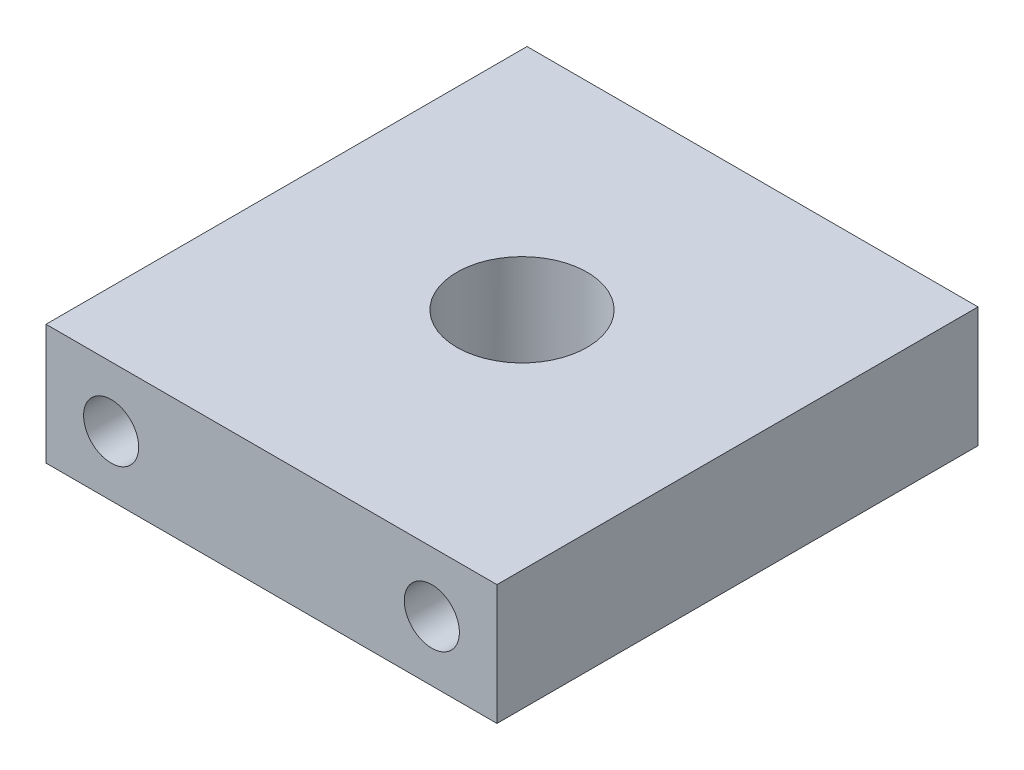
SolidWorks part; units mm, degrees
ref_plane "前视基准面" through (0, 0, 0) normal (0, 0, 1) x (1, 0, 0)
ref_plane "上视基准面" through (0, 0, 0) normal (0, 1, 0) x (1, 0, 0)
ref_plane "右视基准面" through (0, 0, 0) normal (1, 0, 0) x (0, 0, -1)
sketch "草图1" plane through (0, 0, 0) normal (0, 1, 0) x (1, 0, 0)
  line L1 (0, 0) -> (45, 0)
  line L2 (0, 0) -> (0, 48)
  line L3 (0, 48) -> (45, 48)
  line L4 (45, 0) -> (45, 48)
  dimension "D1" = 45
  dimension "D2" = 48
extrude "凸台-拉伸1" add sketch "草图1" along normal blind 12
sketch "草图2" plane through (0, 12, 0) normal (0, 1, 0) x (1, 0, 0)
  line L0 (22.5, 48) -> (22.5, 0) construction
  line L1 (45, 48) -> (0, 48) construction
  line L2 (0, 0) -> (45, 0) construction
  line L3 (0, 25) -> (45, 25) construction
  line L4 (0, 48) -> (0, 0) construction
  line L5 (45, 0) -> (45, 48) construction
  circle A0 centre (22.5, 25) radius 6.5
  dimension "D1" = 13
  dimension "D2" = 25
extrude "切除-拉伸1" cut sketch "草图2" against normal up to surface (12 mm away) up to face at (22.5, 0, -24)
sketch "草图8" plane through (0, 0, 0) normal (0, -1, 0) x (1, 0, 0)
  circle A0 centre (22.5, -25) radius 6.5
  dimension "D1" = 13
hole_wizard "打孔尺寸根据内六角圆柱头螺钉的类型1" positions "草图13" profile "草图12" counterbore size "M5" standard "GB" end condition through all
sketch "草图13" plane through (0, 0, -48) normal (0, 0, -1) x (-1, 0, 0)
  line L0 (-22.5, 12) -> (-22.5, 0) construction
  line L2 (-45, 0) -> (0, 0) construction
  line L4 (-45, 6) -> (-22.5, 6) construction
  line L5 (-45, 12) -> (-45, 0) construction
  point P0 (-38.5, 6)
  point P2 (-6.5, 6)
  dimension "D1" = 32
sketch "草图12" plane through (38.5, 6, -48) normal (1, 0, 0) x (0, 1, 0)
  line L0 (0, 0) -> (0, 48)
  line L1 (0, 48) -> (2.75, 48)
  line L3 (2.75, 48) -> (2.75, 30)
  line L4 (2.75, 30) -> (4.75, 30)
  line L5 (4.75, 30) -> (4.75, 0)
  line L7 (4.75, 0) -> (0, 0)
  line L11 (0, -6.35) -> (0, 107.95) construction
  dimension "通孔孔直径" = 5.5
  dimension "通孔孔深度" = 48
  dimension "柱形沉头孔直径" = 9.5
  dimension "柱形沉头孔深度" = 30
sketch "草图14" plane through (0, 0, 0) normal (0, -1, 0) x (1, 0, 0)
  line L0 (0, 0) -> (45, 0) construction
  line L1 (22.5, 0) -> (22.5, -25) construction
  line L2 (45, -48) -> (0, -48) construction
  circle A0 centre (14.5, -43) radius 3
  circle A1 centre (30.5, -43) radius 3
  dimension "D1" = 5
  dimension "D2" = 6
  dimension "D3" = 16
extrude "切除-拉伸2" cut sketch "草图14" against normal blind 8
